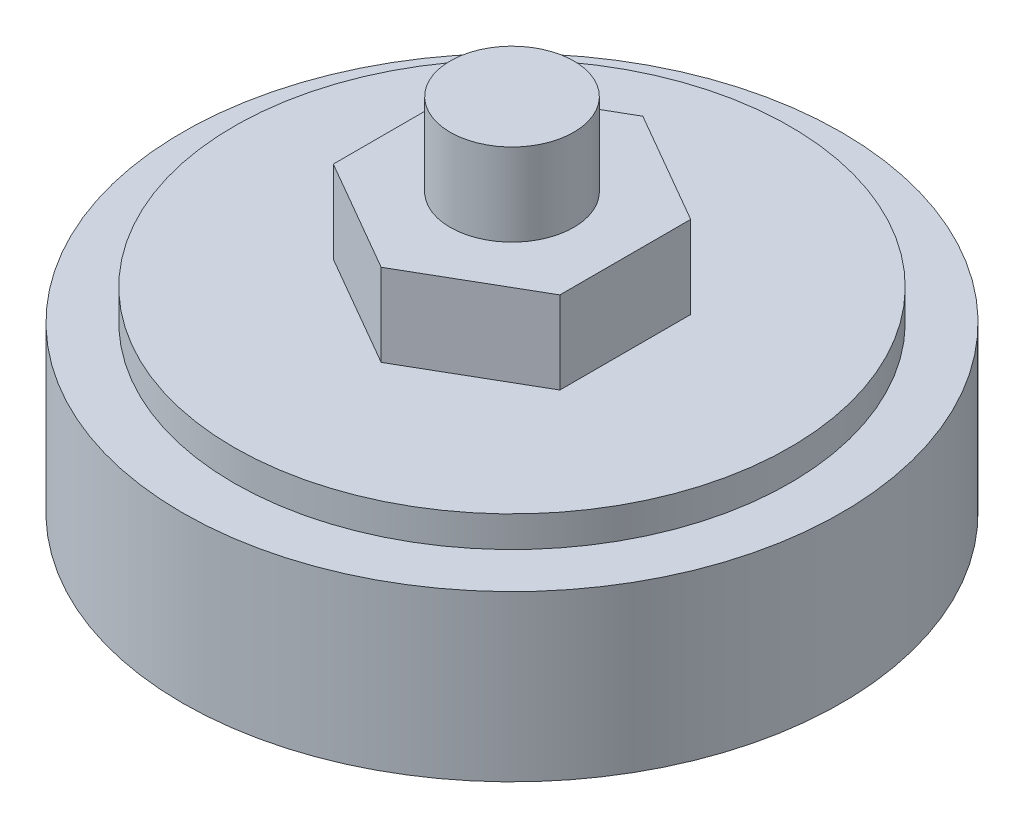
SolidWorks part; units mm, degrees
material "1.4000 (X6Cr13)"
ref_plane "Plan de face" through (0, 0, 0) normal (0, 0, 1) x (1, 0, 0)
ref_plane "Plan de dessus" through (0, 0, 0) normal (0, 1, 0) x (1, 0, 0)
ref_plane "Plan de droite" through (0, 0, 0) normal (1, 0, 0) x (0, 0, -1)
sketch "Esquisse1" plane through (0, 0, 0) normal (0, 1, 0) x (1, 0, 0)
  circle A0 centre (0, 0) radius 8
  dimension "D1" = 16
extrude "Boss.-Extru.1" add sketch "Esquisse1" along normal mid plane 4
sketch "Esquisse2" plane through (0, 0, 0) normal (0, 1, 0) x (1, 0, 0)
  circle A0 centre (0, 0) radius 6.75
  dimension "D1" = 13.5
extrude "Boss.-Extru.2" add sketch "Esquisse2" along normal mid plane 5.5
sketch "Esquisse3" plane through (0, 2.75, 0) normal (0, 1, 0) x (1, 0, 0)
  line L1 (0, 3.1754) -> (-2.75, 1.5877)
  line L2 (-2.75, 1.5877) -> (-2.75, -1.5877)
  line L3 (-2.75, -1.5877) -> (0, -3.1754)
  line L4 (0, -3.1754) -> (2.75, -1.5877)
  line L5 (2.75, -1.5877) -> (2.75, 1.5877)
  line L6 (2.75, 1.5877) -> (0, 3.1754)
  circle A0 centre (0, 0) radius 2.75 construction
  dimension "D1" = 5.5
extrude "Boss.-Extru.3" add sketch "Esquisse3" along normal blind 2
sketch "Esquisse4" plane through (0, 4.75, 0) normal (0, 1, 0) x (1, 0, 0)
  circle A0 centre (0, 0) radius 1.5
  dimension "D1" = 3
extrude "Boss.-Extru.4" add sketch "Esquisse4" along normal blind 2
